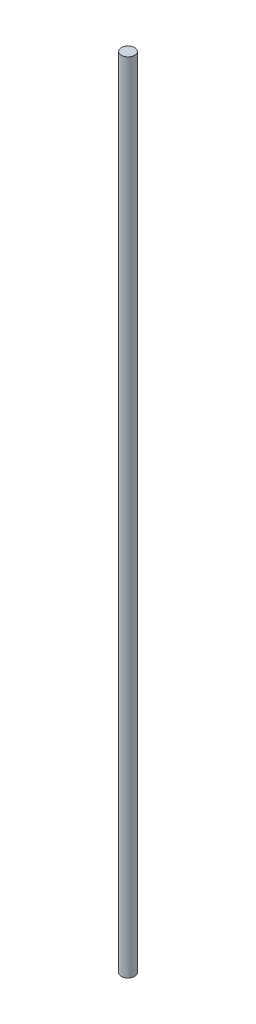
SolidWorks part; units mm, degrees
material "Plain Carbon Steel"
ref_plane "Front Plane" through (0, 0, 0) normal (0, 0, 1) x (1, 0, 0)
ref_plane "Top Plane" through (0, 0, 0) normal (0, 1, 0) x (1, 0, 0)
ref_plane "Right Plane" through (0, 0, 0) normal (1, 0, 0) x (0, 0, -1)
sketch "Sketch1" plane through (0, 0, 0) normal (0, 1, 0) x (1, 0, 0)
  circle A0 centre (0, 0) radius 5
  dimension "D1" = 10
extrude "Boss-Extrude1" add sketch "Sketch1" along normal blind 600
